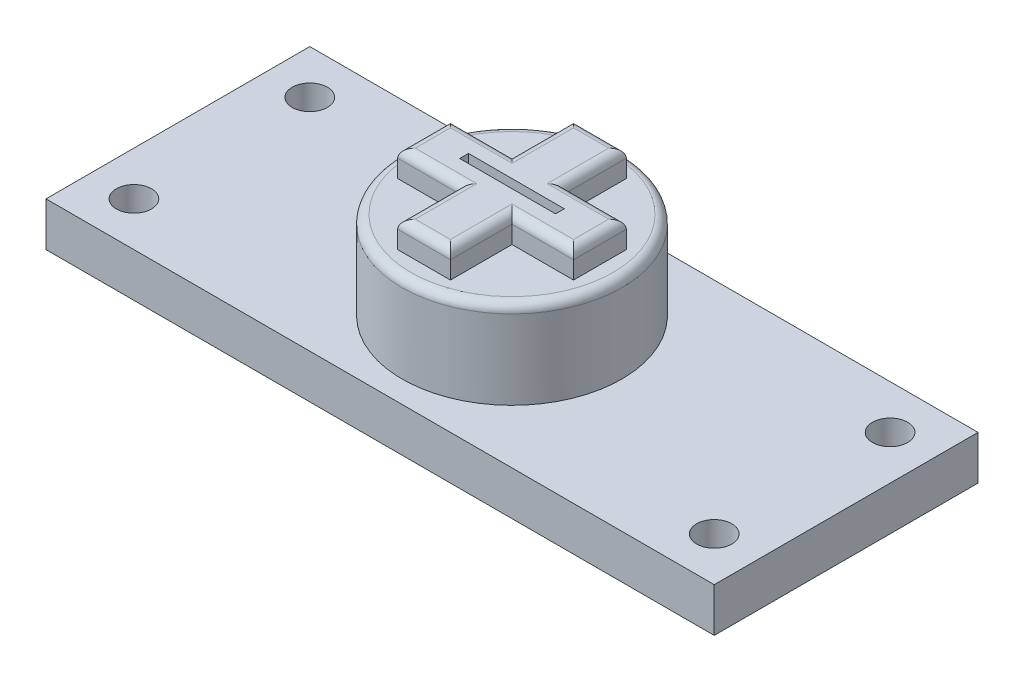
SolidWorks part; units mm, degrees
ref_plane "Front Plane" through (0, 0, 0) normal (0, 0, 1) x (1, 0, 0)
ref_plane "Top Plane" through (0, 0, 0) normal (0, 1, 0) x (1, 0, 0)
ref_plane "Right Plane" through (0, 0, 0) normal (1, 0, 0) x (0, 0, -1)
sketch "Sketch1" plane through (0, 0, 0) normal (0, 1, 0) x (1, 0, 0)
  line L1 (-3800, 1500) -> (3800, 1500)
  line L2 (-3800, 1500) -> (-3800, -1500)
  line L3 (-3800, -1500) -> (3800, -1500)
  line L4 (3800, 1500) -> (3800, -1500)
  line L5 (-3800, 1500) -> (3800, -1500) construction
  line L6 (-3800, -1500) -> (3800, 1500) construction
  point P0 (0, 0)
  dimension "D1" = 7600
  dimension "D2" = 3000
extrude "Boss-Extrude1" add sketch "Sketch1" along normal blind 500 contours L2 L3 L4 L1
sketch "Sketch2" plane through (0, 500, 0) normal (0, 1, 0) x (1, 0, 0)
  line L0 (-3800, 1500) -> (3800, 1500) construction
  line L1 (3800, 1500) -> (3800, -1500) construction
  line L2 (-3800, -1500) -> (3800, -1500) construction
  line L3 (-3800, 1500) -> (-3800, -1500) construction
  circle A0 centre (-3300, -1000) radius 200
  circle A1 centre (-3300, 1000) radius 200
  circle A2 centre (3300, 1000) radius 200
  circle A3 centre (3300, -1000) radius 200
  dimension "D1" = 400
  dimension "D2" = 400
  dimension "D3" = 400
  dimension "D4" = 400
  dimension "D5" = 500
  dimension "D6" = 500
  dimension "D7" = 500
  dimension "D8" = 500
  dimension "D9" = 500
  dimension "D10" = 500
  dimension "D11" = 500
  dimension "D12" = 500
extrude "Cut-Extrude1" cut sketch "Sketch2" against normal blind 1000
sketch "Sketch3" plane through (0, 500, 0) normal (0, 1, 0) x (1, 0, 0)
  circle A0 centre (0, 0) radius 1250
  dimension "D1" = 2500
extrude "Boss-Extrude2" add sketch "Sketch3" along normal blind 1000
sketch "Sketch4" plane through (0, 1500, 0) normal (0, 1, 0) x (1, 0, 0)
  line L0 (-300, -300) -> (-300, -1000)
  line L1 (-300, 1000) -> (300, 1000)
  line L2 (-300, 1000) -> (-300, 300)
  line L3 (-300, -1000) -> (300, -1000)
  line L4 (300, 1000) -> (300, 300)
  line L5 (-300, 1000) -> (300, -1000) construction
  line L6 (-300, -1000) -> (300, 1000) construction
  line L7 (1000, -300) -> (300, -300)
  line L8 (1000, -300) -> (1000, 300)
  line L9 (1000, 300) -> (300, 300)
  line L10 (-1000, -300) -> (-1000, 300)
  line L11 (1000, -300) -> (-1000, 300) construction
  line L12 (1000, 300) -> (-1000, -300) construction
  line L13 (300, -300) -> (300, -1000)
  line L14 (-300, -300) -> (-1000, -300)
  line L15 (-300, 300) -> (-1000, 300)
  point P0 (0, 0)
  point P6 (0, 0)
  dimension "D1" = 600
  dimension "D2" = 600
  dimension "D3" = 2000
  dimension "D4" = 2000
extrude "Boss-Extrude3" add sketch "Sketch4" along normal blind 300
fillet "Fillet1" radius 100 12 edges at (0, 1800, 1000) (-300, 1800, 650) (-650, 1800, 300) (-1000, 1800, 0) (-650, 1800, -300) (-300, 1800, -650) (0, 1800, -1000) (300, 1800, -650) (650, 1800, -300) (1000, 1800, 0) (650, 1800, 300) (300, 1800, 650)
fillet "Fillet2" radius 100 1 edges at (0, 1500, 1250)
sketch "Sketch6" plane through (0, 1800, 0) normal (0, 1, 0) x (1, 0, 0)
  line L1 (-545.25, 50) -> (545.25, 50)
  line L2 (-545.25, 50) -> (-545.25, -50)
  line L3 (-545.25, -50) -> (545.25, -50)
  line L4 (545.25, 50) -> (545.25, -50)
  line L5 (-545.25, 50) -> (545.25, -50) construction
  line L6 (-545.25, -50) -> (545.25, 50) construction
  point P0 (0, 0)
  dimension "D1" = 1090.5
  dimension "D2" = 100
extrude "Cut-Extrude2" cut sketch "Sketch6" against normal blind 100
